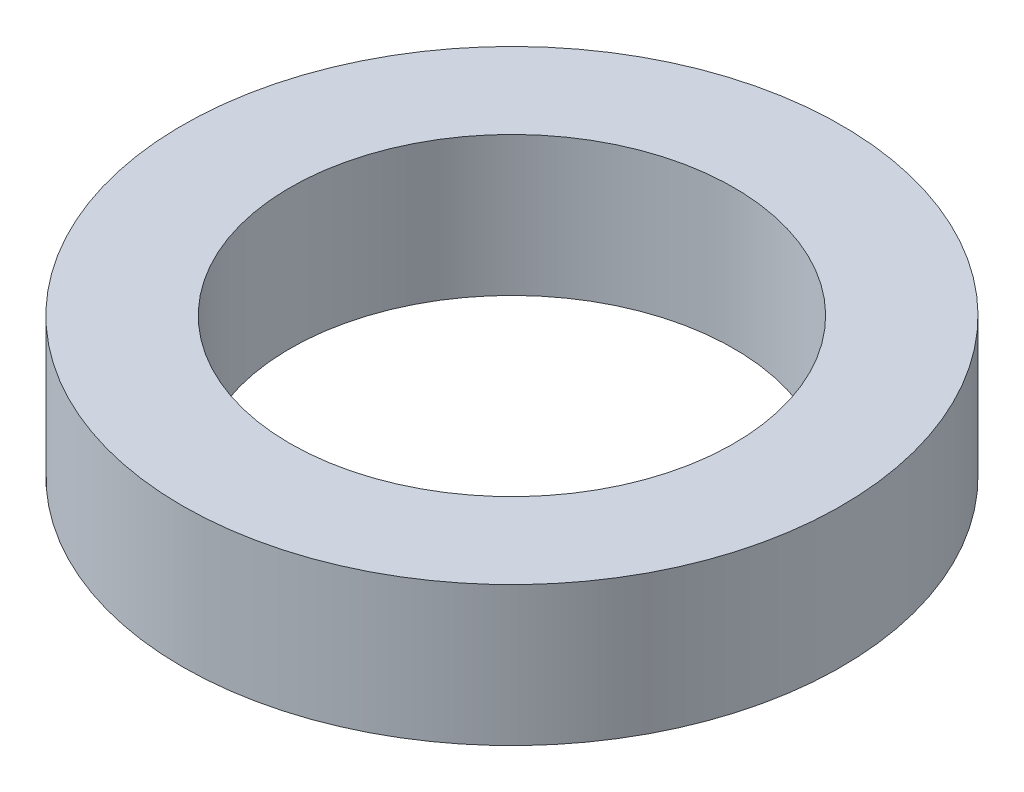
SolidWorks part; units mm, degrees
ref_plane "Front Plane" through (0, 0, 0) normal (0, 0, 1) x (1, 0, 0)
ref_plane "Top Plane" through (0, 0, 0) normal (0, 1, 0) x (1, 0, 0)
ref_plane "Right Plane" through (0, 0, 0) normal (1, 0, 0) x (0, 0, -1)
sketch "Sketch1" plane through (0, 0, 0) normal (0, 1, 0) x (1, 0, 0)
  circle A0 centre (0, 0) radius 17.5
  circle A1 centre (0, 0) radius 26
  dimension "D1" = 35
  dimension "D2" = 52
extrude "Boss-Extrude1" add sketch "Sketch1" along normal blind 11
